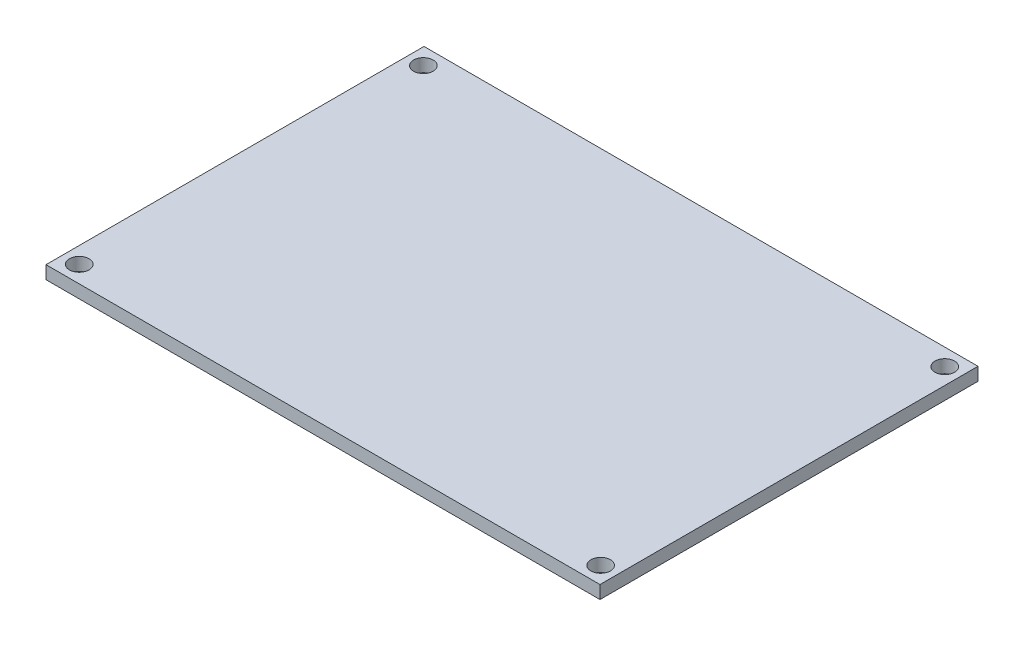
SolidWorks part; units mm, degrees
ref_plane "前视基准面" through (0, 0, 0) normal (0, 0, 1) x (1, 0, 0)
ref_plane "上视基准面" through (0, 0, 0) normal (0, 1, 0) x (1, 0, 0)
ref_plane "右视基准面" through (0, 0, 0) normal (1, 0, 0) x (0, 0, -1)
other "Configuration Table"
sketch "草图1" plane through (0, 0, 0) normal (0, 1, 0) x (1, 0, 0)
  line L1 (-42.5, -29) -> (42.5, -29)
  line L2 (-42.5, -29) -> (-42.5, 29)
  line L3 (-42.5, 29) -> (42.5, 29)
  line L4 (42.5, -29) -> (42.5, 29)
  line L5 (-42.5, -29) -> (42.5, 29) construction
  line L6 (-42.5, 29) -> (42.5, -29) construction
  point P0 (0, 0)
  dimension "D1" = 85
  dimension "D2" = 58
extrude "凸台-拉伸1" add sketch "草图1" along normal blind 2
sketch "草图2" plane through (0, 2, 0) normal (0, 1, 0) x (1, 0, 0)
  line L1 (-40, -26.4) -> (40, -26.4) construction
  line L2 (-40, -26.4) -> (-40, 26.4) construction
  line L3 (-40, 26.4) -> (40, 26.4) construction
  line L4 (40, -26.4) -> (40, 26.4) construction
  line L5 (-40, -26.4) -> (40, 26.4) construction
  line L6 (-40, 26.4) -> (40, -26.4) construction
  circle A0 centre (-40, 26.4) radius 1.5
  circle A1 centre (40, 26.4) radius 1.5
  circle A2 centre (40, -26.4) radius 1.5
  circle A3 centre (-40, -26.4) radius 1.5
  point P0 (0, 0)
  dimension "D3" = 3
  dimension "D1" = 80
  dimension "D2" = 52.8
extrude "切除-拉伸1" cut sketch "草图2" against normal blind 2
